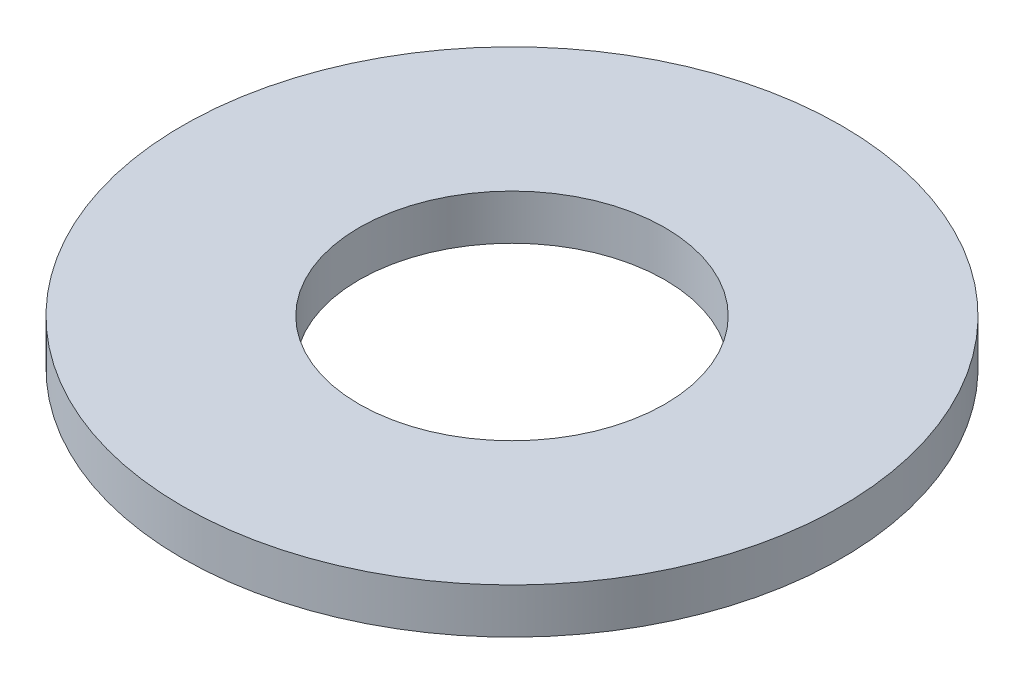
SolidWorks part; units mm, degrees
material "AISI 4130 Steel, normalized at 870C"
ref_plane "Front Plane" through (0, 0, 0) normal (0, 0, 1) x (1, 0, 0)
ref_plane "Top Plane" through (0, 0, 0) normal (0, 1, 0) x (1, 0, 0)
ref_plane "Right Plane" through (0, 0, 0) normal (1, 0, 0) x (0, 0, -1)
sketch "Sketch1" plane through (0, 0, 0) normal (0, 1, 0) x (1, 0, 0)
  circle A0 centre (0, 0) radius 11.1125
  dimension "OD" = 22.225
extrude "Boss-Extrude1" add sketch "Sketch1" along normal blind 1.524
sketch "Sketch5" plane through (0, 1.524, 0) normal (0, 1, 0) x (-1, 0, 0)
  circle A0 centre (0, 0) radius 5.1562
  dimension "ID" = 10.3124
extrude "Cut-Extrude1" cut sketch "Sketch5" against normal through all
